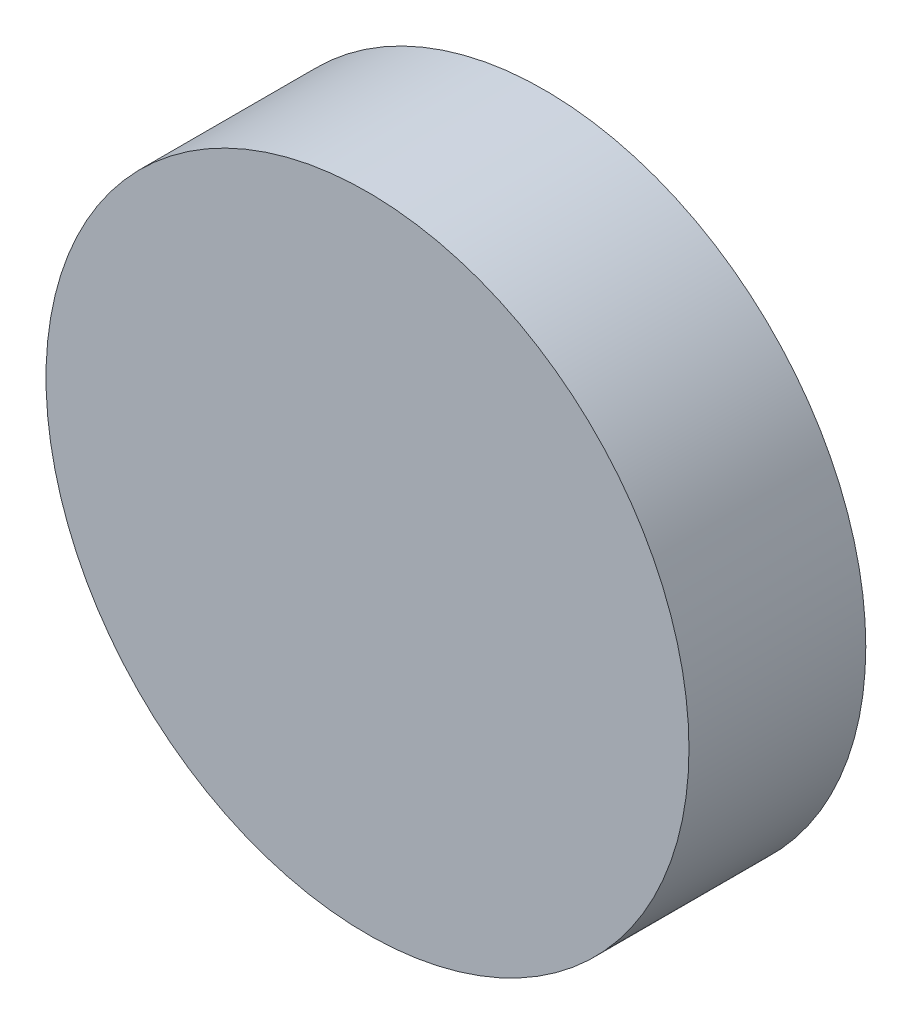
SolidWorks part; units mm, degrees
ref_plane "Front Plane" through (0, 0, 0) normal (0, 0, 1) x (1, 0, 0)
ref_plane "Top Plane" through (0, 0, 0) normal (0, 1, 0) x (1, 0, 0)
ref_plane "Right Plane" through (0, 0, 0) normal (1, 0, 0) x (0, 0, -1)
sketch "Sketch1" plane through (0, 0, 0) normal (0, 0, 1) x (1, 0, 0)
  circle A0 centre (0, 0) radius 20
  dimension "D1" = 40
extrude "Boss-Extrude1" add sketch "Sketch1" along normal blind 11
